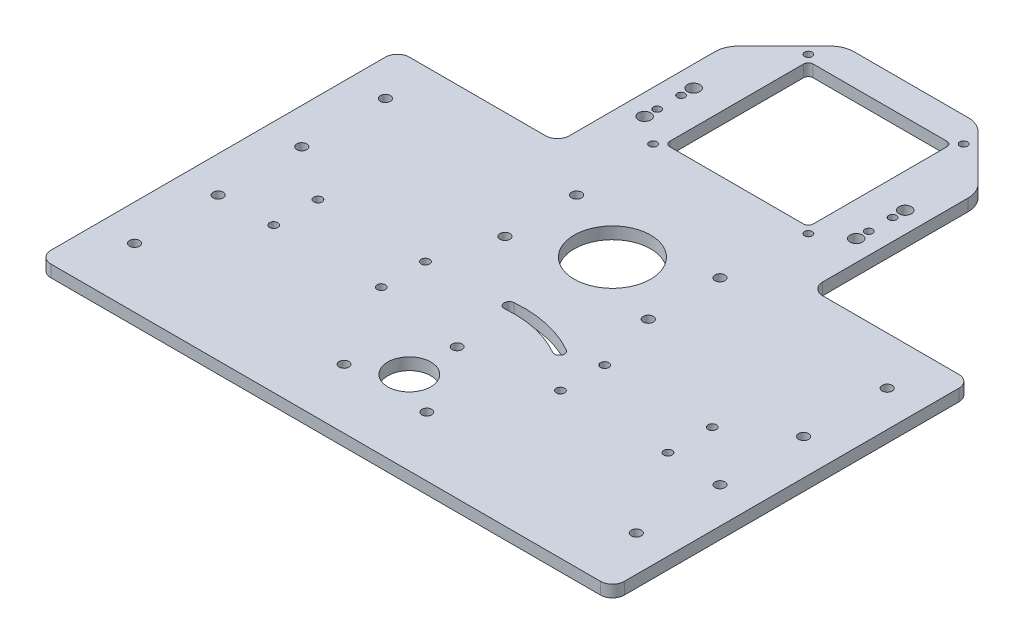
SolidWorks part; units mm, degrees
ref_plane "前视基准面" through (0, 0, 0) normal (0, 0, 1) x (1, 0, 0)
ref_plane "上视基准面" through (0, 0, 0) normal (0, 1, 0) x (1, 0, 0)
ref_plane "右视基准面" through (0, 0, 0) normal (1, 0, 0) x (0, 0, -1)
sketch "草图1" plane through (0, 0, 0) normal (0, 1, 0) x (1, 0, 0)
  line L0 (-105, 32.5) -> (-105, -32.5) construction
  line L1 (-120, 32.5) -> (120, 32.5)
  line L2 (-120, 32.5) -> (-120, -32.5)
  line L3 (-120, -32.5) -> (120, -32.5)
  line L4 (120, 32.5) -> (120, -32.5)
  line L5 (-120, 32.5) -> (120, -32.5) construction
  line L6 (-120, -32.5) -> (120, 32.5) construction
  line L7 (0, 0) -> (0, 32.5) construction
  line L8 (-10, 12.5) -> (10, 12.5) construction
  line L10 (-30, 27.5) -> (30, 27.5) construction
  line L11 (-30, 27.5) -> (-30, -2.5) construction
  line L12 (-30, -2.5) -> (30, -2.5) construction
  line L13 (30, 27.5) -> (30, -2.5) construction
  line L14 (-30, 27.5) -> (30, -2.5) construction
  line L15 (-30, -2.5) -> (30, 27.5) construction
  circle A0 centre (-105, 22.5) radius 2.1
  circle A1 centre (-105, -12.5) radius 2.1
  circle A2 centre (105, -12.5) radius 2.1
  circle A3 centre (105, 22.5) radius 2.1
  circle A6 centre (0, 12.5) radius 16
  circle A7 centre (-30, 27.5) radius 2.1
  circle A8 centre (30, 27.5) radius 2.1
  circle A9 centre (30, -2.5) radius 2.1
  circle A10 centre (-30, -2.5) radius 2.1
  point P0 (0, 0)
  point P21 (0, 12.5)
  dimension "D3" = 4.2
  dimension "D4" = 4.2
  dimension "D7" = 30
  dimension "D8" = 60
  dimension "D10" = 32
  dimension "D12" = 4.2
  dimension "D13" = 4.2
  dimension "D1" = 240
  dimension "D2" = 65
  dimension "D5" = 35
  dimension "D6" = 20
  dimension "D9" = 20
  dimension "D11" = 20
  dimension "D14" = 15
extrude "凸台-拉伸1" add sketch "草图1" along normal blind 5
sketch "草图2" plane through (0, 5, 0) normal (0, 1, 0) x (1, 0, 0)
  line L0 (0, 0) -> (0, -72.5) construction
  line L1 (-35, -72.5) -> (-35, -32.5)
  line L2 (-120, -32.5) -> (120, -32.5) construction
  line L3 (35, -72.5) -> (35, -32.5)
  line L4 (35, -32.5) -> (-35, -32.5)
  line L5 (-1099.4611, -70.5) -> (48900.5389, -70.5) construction
  line L6 (-53, -32.5) -> (-53, -107.5)
  line L7 (-53, -107.5) -> (0, -107.5)
  line L8 (53, -107.5) -> (0, -107.5)
  line L9 (53, -32.5) -> (53, -107.5)
  line L10 (35, -72.5) -> (35, -32.5)
  line L11 (-44.2705, -45.5) -> (-44.2705, -95.5) construction
  line L12 (-1053.018, -107.5) -> (48946.982, -107.5) construction
  line L13 (-120, -32.5) -> (-120, -107.5)
  line L14 (-120, 32.5) -> (-120, -32.5) construction
  line L15 (-120, -107.5) -> (-53, -107.5)
  line L16 (120, -32.5) -> (120, -107.5)
  line L17 (120, -107.5) -> (53, -107.5)
  line L18 (-105, -1012.5) -> (-105, 48987.5) construction
  line L19 (-1120, 0) -> (48880, 0) construction
  line L20 (-120, 32.5) -> (-120, -32.5) construction
  line L21 (-44.2705, -45.5) -> (-44.2705, 122.3297) construction
  line L23 (53, 32.5) -> (53, 107.5)
  line L26 (-53, 32.5) -> (-53, 107.5)
  line L27 (-53, 32.5) -> (53, 32.5)
  line L29 (-53, 107.5) -> (-53, 137.5)
  line L30 (-53, 137.5) -> (53, 137.5)
  line L31 (53, 137.5) -> (53, 107.5)
  line L32 (-44.2705, 80.5) -> (0, 80.5) construction
  circle A0 centre (0, -72.5) radius 35
  circle A1 centre (0, -72.5) radius 9
  circle A2 centre (0, -52.5) radius 2.05
  circle A3 centre (17.3205, -82.5) radius 2.05
  circle A4 centre (-17.3205, -82.5) radius 2.05
  circle A5 centre (-44.2705, -45.5) radius 1.6
  circle A6 centre (-44.2705, -95.5) radius 1.6
  circle A7 centre (44.2705, -95.5) radius 1.6
  circle A8 centre (44.2705, -45.5) radius 1.6
  circle A9 centre (-44.2705, -80.75) radius 2.6
  circle A10 centre (-44.2705, -60.25) radius 2.6
  circle A11 centre (-44.2705, -75.5) radius 1.6
  circle A12 centre (-44.2705, -65.5) radius 1.6
  circle A13 centre (44.2705, -65.5) radius 1.6
  circle A14 centre (44.2705, -75.5) radius 1.6
  circle A15 centre (44.2705, -60.25) radius 2.6
  circle A16 centre (44.2705, -80.75) radius 2.6
  circle A17 centre (-105, -47.5) radius 2.1
  circle A18 centre (-105, -12.5) radius 2.1 construction
  circle A19 centre (-105, -12.5) radius 2.1 construction
  circle A20 centre (-105, -82.5) radius 2.1
  circle A21 centre (105, -82.5) radius 2.1
  circle A22 centre (105, -47.5) radius 2.1
  circle A38 centre (0, 72.5) radius 9
  circle A39 centre (-105, 22.5) radius 2.1 construction
  circle A40 centre (-105, 22.5) radius 2.1 construction
  circle A41 centre (-44.2705, 75.5) radius 1.6
  circle A42 centre (-44.2705, 70.25) radius 2.6
  circle A43 centre (-44.2705, 85.5) radius 1.6
  circle A44 centre (-44.2705, 90.75) radius 2.6
  circle A45 centre (44.2705, 90.75) radius 2.6
  circle A46 centre (44.2705, 85.5) radius 1.6
  circle A47 centre (44.2705, 70.25) radius 2.6
  circle A48 centre (44.2705, 75.5) radius 1.6
  point P20 (0, -72.5)
  point P29 (-44.2705, -70.5)
  point P51 (44.2705, -70.5)
  point P79 (-120, 0)
  dimension "D1" = 70
  dimension "D2" = 18
  dimension "D3" = 4.1
  dimension "D11" = 3.2
  dimension "D12" = 3.2
  dimension "D8" = 5.2
  dimension "D15" = 3.2
  dimension "D16" = 4.2
  dimension "D18" = 35
  dimension "D19" = 4.2
  dimension "D23" = 5.2
  dimension "D25" = 3.2
  dimension "D5" = 20
  dimension "D6" = 40
  dimension "D7" = 38
  dimension "D9" = 18
  dimension "D10" = 50
  dimension "D13" = 10.25
  dimension "D14" = 5
  dimension "D17" = 35
  dimension "D20" = 30
  dimension "D21" = 20
  dimension "D22" = 58
  dimension "D24" = 10.25
  dimension "D26" = 5
  dimension "D4" = 3
extrude "凸台-拉伸2" add sketch "草图2" against normal up to surface (5 mm away)
fillet "圆角1" [suppressed] radius 20
fillet "圆角4" [suppressed] radius 3
sketch "草图3" plane through (0, 5, 0) normal (0, 1, 0) x (1, 0, 0)
  line L0 (0, -72.5) -> (0, -26.5) construction
  line L1 (-4.0092, -26.675) -> (0, -72.5) construction
  line L2 (23, -32.6628) -> (0, -72.5) construction
  circle A0 centre (0, 12.5) radius 16 construction
  circle A1 centre (0, 12.5) radius 16 construction
  circle A2 centre (0, -72.5) radius 9 construction
  circle A3 centre (0, -72.5) radius 9 construction
  arc A6 (23, -32.6628) -> (-4.0092, -26.675) centre (0, -72.5) ccw construction
  arc A7 (24.05, -30.8442) -> (-4.1922, -24.583) centre (0, -72.5) ccw
  arc A8 (21.95, -34.4815) -> (-3.8261, -28.7671) centre (0, -72.5) ccw
  arc A9 (21.95, -34.4815) -> (24.05, -30.8442) centre (23, -32.6628) ccw
  arc A10 (-4.1922, -24.583) -> (-3.8261, -28.7671) centre (-4.0092, -26.675) ccw
  point P11 (9.9562, -27.5904)
  dimension "D1" = 46
  dimension "D4" = 2.1
  dimension "D2" = 30
  dimension "D3" = 5
extrude "切除-拉伸1" cut sketch "草图3" against normal blind 10
sketch "草图4" plane through (0, 5, 0) normal (0, 1, 0) x (1, 0, 0)
  line L1 (-120, 32.5) -> (120, 32.5)
  line L2 (-120, 32.5) -> (-120, 42.5)
  line L3 (-120, 42.5) -> (120, 42.5)
  line L4 (120, 32.5) -> (120, 42.5)
  dimension "D1" = 10
extrude "凸台-拉伸3" add sketch "草图4" against normal up to surface (5 mm away) up to face at (9.6575, 0, 28.9379)
fillet "圆角5" radius 5 4 edges at (120, 2.5, -42.5) (-120, 2.5, -42.5) (120, 2.5, 107.5) (-120, 2.5, 107.5)
sketch "草图6" plane through (0, 0, 0) normal (0, -1, 0) x (1, 0, 0)
  line L0 (-53, -42.5) -> (53, -42.5) construction
  line L1 (0, -42.5) -> (0, -94.5) construction
  line L2 (0, -94.5) -> (99.2931, -94.5) construction
  line L3 (-32.5, -62) -> (32.5, -62) construction
  line L4 (-32.5, -62) -> (-32.5, -127) construction
  line L5 (-32.5, -127) -> (32.5, -127) construction
  line L6 (32.5, -62) -> (32.5, -127) construction
  line L7 (-32.5, -62) -> (32.5, -127) construction
  line L8 (-32.5, -127) -> (32.5, -62) construction
  line L9 (-32.5, -127) -> (32.5, -127) construction
  line L11 (-30, -64.5) -> (30, -64.5)
  line L12 (-30, -64.5) -> (-30, -124.5)
  line L13 (-30, -124.5) -> (30, -124.5)
  line L14 (30, -64.5) -> (30, -124.5)
  line L15 (-30, -64.5) -> (30, -124.5) construction
  line L16 (-30, -124.5) -> (30, -64.5) construction
  circle A0 centre (-32.5, -62) radius 1.6
  circle A1 centre (32.5, -62) radius 1.6
  circle A2 centre (32.5, -127) radius 1.6
  circle A3 centre (-32.5, -127) radius 1.6
  point P6 (0, -94.5)
  dimension "D3" = 3.2
  dimension "D4" = 3.2
  dimension "D1" = 65
  dimension "D2" = 65
  dimension "D5" = 60
  dimension "D6" = 52
extrude "切除-拉伸2" cut sketch "草图6" against normal blind 10
fillet "圆角6" radius 5 2 edges at (53, 2.5, -42.5) (-53, 2.5, -42.5)
chamfer "倒角1" distance 25 angle 45 2 edges at (53, 2.5, -137.5) (-53, 2.5, -137.5)
sketch "草图7" plane through (0, 5, 0) normal (0, 1, 0) x (1, 0, 0)
  line L0 (120, -102.5) -> (120, 37.5) construction
  line L1 (37.5, -28.25) -> (82.5, -28.25) construction
  line L2 (37.5, -28.25) -> (37.5, -46.75) construction
  line L3 (37.5, -46.75) -> (82.5, -46.75) construction
  line L4 (82.5, -28.25) -> (82.5, -46.75) construction
  line L5 (37.5, -28.25) -> (82.5, -46.75) construction
  line L6 (37.5, -46.75) -> (82.5, -28.25) construction
  line L7 (115, 42.5) -> (58, 42.5) construction
  line L8 (0, 0) -> (0, 72.8265) construction
  line L9 (-37.5, -46.75) -> (-82.5, -28.25) construction
  line L10 (-37.5, -28.25) -> (-82.5, -46.75) construction
  line L11 (-82.5, -28.25) -> (-82.5, -46.75) construction
  line L12 (-37.5, -46.75) -> (-82.5, -46.75) construction
  line L13 (-37.5, -28.25) -> (-37.5, -46.75) construction
  line L14 (-37.5, -28.25) -> (-82.5, -28.25) construction
  circle A0 centre (37.5, -28.25) radius 1.75
  circle A1 centre (37.5, -46.75) radius 1.75
  circle A2 centre (82.5, -28.25) radius 1.75
  circle A3 centre (82.5, -46.75) radius 1.75
  circle A4 centre (-82.5, -46.75) radius 1.75
  circle A5 centre (-82.5, -28.25) radius 1.75
  circle A6 centre (-37.5, -46.75) radius 1.75
  circle A7 centre (-37.5, -28.25) radius 1.75
  point P0 (60, -37.5)
  point P24 (-60, -37.5)
  dimension "D5" = 3.5
  dimension "D6" = 3.5
  dimension "D7" = 3.5
  dimension "D8" = 3.5
  dimension "D1" = 60
  dimension "D2" = 45
  dimension "D3" = 18.5
  dimension "D4" = 80
extrude "切除-拉伸3" cut sketch "草图7" against normal blind 10
fillet "圆角7" radius 10 4 edges at (53, 2.5, -112.5) (28, 2.5, -137.5) (-28, 2.5, -137.5) (-53, 2.5, -112.5)
fillet "圆角8" radius 2 4 edges at (30, 2.5, -64.5) (-30, 2.5, -64.5) (30, 2.5, -124.5) (-30, 2.5, -124.5)
